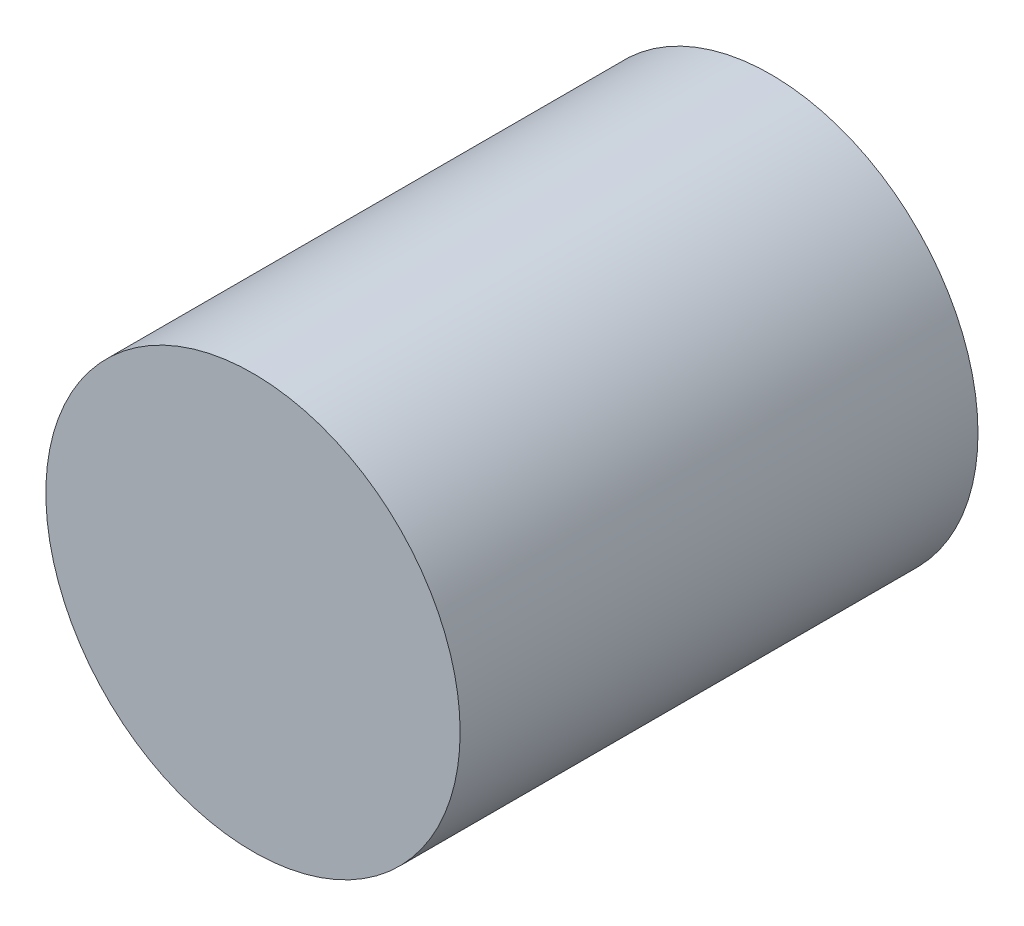
SolidWorks part; units mm, degrees
ref_plane "前视基准面" through (0, 0, 0) normal (0, 0, 1) x (1, 0, 0)
ref_plane "上视基准面" through (0, 0, 0) normal (0, 1, 0) x (1, 0, 0)
ref_plane "右视基准面" through (0, 0, 0) normal (1, 0, 0) x (0, 0, -1)
other "Configuration Table"
sketch "草图1" plane through (0, 0, 0) normal (0, 0, 1) x (1, 0, 0)
  circle A0 centre (0, 0) radius 20
extrude "凸台-拉伸1" add sketch "草图1" against normal blind 50
